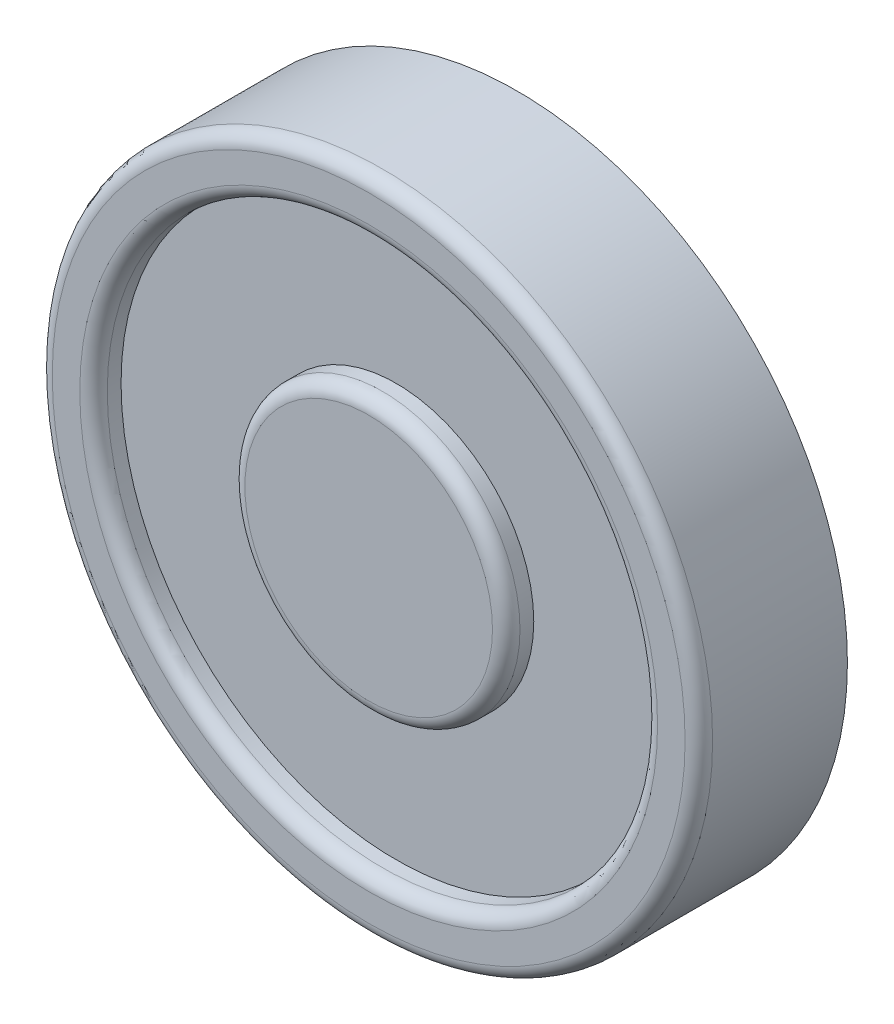
SolidWorks part; units mm, degrees
ref_plane "Front Plane" through (0, 0, 0) normal (0, 0, 1) x (1, 0, 0)
ref_plane "Top Plane" through (0, 0, 0) normal (0, 1, 0) x (1, 0, 0)
ref_plane "Right Plane" through (0, 0, 0) normal (1, 0, 0) x (0, 0, -1)
sketch "Sketch1" plane through (0, 0, 0) normal (0, 0, 1) x (1, 0, 0)
  circle A0 centre (-2.6279, 3.3722) radius 2.4
  dimension "D1" = 4.8
extrude "Boss-Extrude1" add sketch "Sketch1" along normal blind 1.08
sketch "Sketch2" plane through (0, 0, 1.08) normal (0, 0, 1) x (1, 0, 0)
  circle A0 centre (-2.6279, 3.3722) radius 2
  circle A1 centre (-2.6279, 3.3722) radius 2.4 construction
  circle A2 centre (-2.6279, 3.3722) radius 1
  dimension "D1" = 0
  dimension "D2" = 4
  dimension "D3" = 0
  dimension "D4" = 2
extrude "Cut-Extrude1" cut sketch "Sketch2" against normal blind 0.2
fillet "Fillet2" radius 0.1 3 edges at (-1.6279, 3.3722, 1.08) (-0.2279, 3.3722, 1.08) (-0.6279, 3.3722, 1.08)
sketch "Sketch3" plane through (0, 0, 0) normal (0, 0, -1) x (-1, 0, 0)
  circle A0 centre (2.6279, 3.3722) radius 0.5
  circle A1 centre (2.6279, 3.3722) radius 2.4 construction
  dimension "D1" = 0
  dimension "D2" = 1
extrude "Cut-Extrude2" cut sketch "Sketch3" against normal blind 0.2
